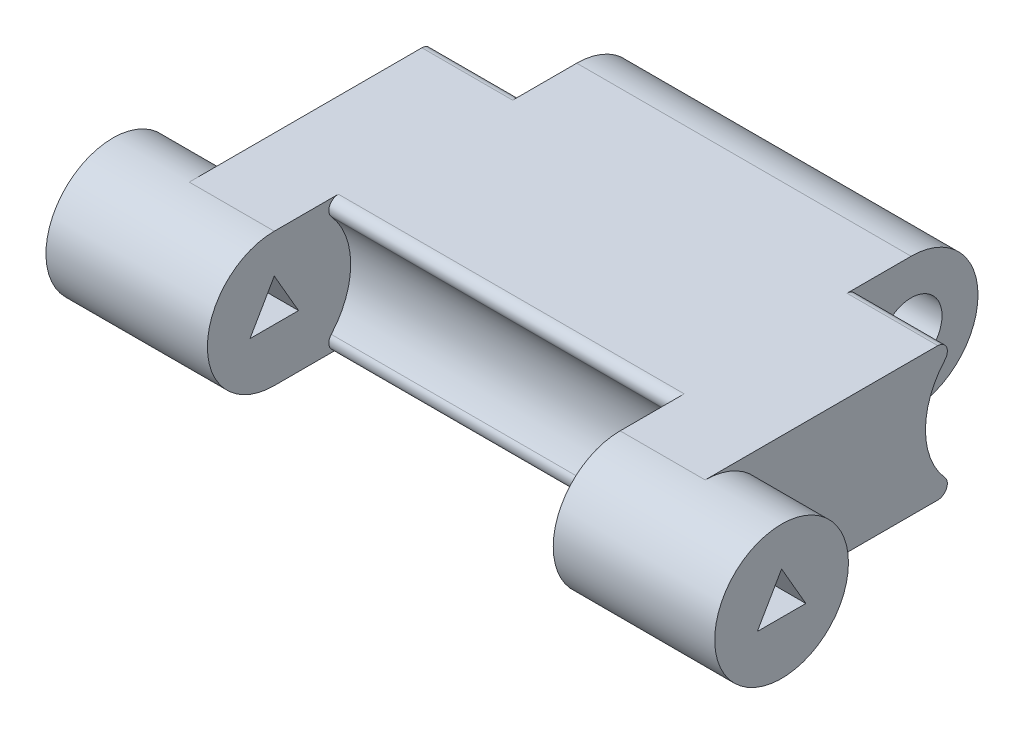
SolidWorks part; units mm, degrees
ref_plane "Спереди" through (0, 0, 0) normal (0, 0, 1) x (1, 0, 0)
ref_plane "Сверху" through (0, 0, 0) normal (0, 1, 0) x (1, 0, 0)
ref_plane "Справа" through (0, 0, 0) normal (1, 0, 0) x (0, 0, -1)
sketch "Эскиз1" plane through (0, 0, 0) normal (1, 0, 0) x (0, 0, -1)
  line L0 (-7.765, 3.5) -> (7.765, 3.5) construction
  line L1 (-7.765, 7) -> (7.765, 7)
  line L2 (-7.765, 0) -> (7.765, 0)
  arc A0 (-7.765, 7) -> (-7.765, 0) centre (-7.765, 3.5) ccw
  arc A1 (7.765, 0) -> (7.765, 7) centre (7.765, 3.5) ccw
  point P2 (0, 3.5)
  dimension "D1" = 15.53
  dimension "D2" = 7
extrude "Бобышка-Вытянуть1" add sketch "Эскиз1" along normal mid plane 35
sketch "Эскиз3" plane through (17.5, 0, 0) normal (1, 0, 0) x (0, 0, -1)
  line L0 (7.765, 7) -> (-7.765, 7) construction
  line L1 (-12, 8) -> (12, 8)
  line L2 (-12, 8) -> (-12, -1)
  line L3 (-12, -1) -> (12, -1)
  line L4 (12, 8) -> (12, -1)
  line L5 (-12, 8) -> (12, -1) construction
  line L6 (-12, -1) -> (12, 8) construction
  line L7 (-7.765, 0) -> (7.765, 0) construction
  circle A0 centre (-7.765, 3.5) radius 3.5
  arc A1 (-7.765, 7) -> (-7.765, 0) centre (-7.765, 3.5) ccw construction
  point P9 (0, 3.5)
  dimension "D1" = 1
  dimension "D2" = 1
  dimension "D3" = 12
  dimension "D4" = 24
extrude "Вырез-Вытянуть1" cut sketch "Эскиз3" against normal blind 4
mirror "Зеркальное отражение1" about plane through (0, 0, 0) normal (1, 0, 0) of "Вырез-Вытянуть1"
sketch "Эскиз6" plane through (0, 0, 0) normal (1, 0, 0) x (0, 0, -1)
  circle A0 centre (-7.765, 3.5) radius 4
  circle A1 centre (-7.765, 3.5) radius 3.5 construction
  dimension "D1" = 8
extrude "Вырез-Вытянуть2" cut sketch "Эскиз6" against normal mid plane 18.1
sketch "Эскиз7" plane through (13.5, 0, 0) normal (1, 0, 0) x (0, 0, -1)
  circle A0 centre (7.765, 3.5) radius 4
  arc A1 (7.765, 0) -> (7.765, 7) centre (7.765, 3.5) ccw construction
  dimension "D2" = 8
  dimension "D1" = 0
extrude "Вырез-Вытянуть3" cut sketch "Эскиз7" against normal blind 4.75
mirror "Зеркальное отражение2" about plane through (0, 0, 0) normal (1, 0, 0) of "Вырез-Вытянуть3"
sketch "Эскиз8" plane through (17.5, 0, 0) normal (1, 0, 0) x (0, 0, -1)
  line L0 (-9.0352, 2.7667) -> (-7.765, 4.9667)
  line L1 (-7.765, 4.9667) -> (-6.4948, 2.7667)
  line L2 (-6.4948, 2.7667) -> (-9.0352, 2.7667)
  circle A1 centre (7.765, 3.5) radius 1.6167
  arc A2 (7.765, 0) -> (7.765, 7) centre (7.765, 3.5) ccw construction
  circle A4 centre (-7.765, 3.5) radius 1.4667 construction
  circle A5 centre (7.765, 3.5) radius 1.4667 construction
  dimension "D1" = 0.15
  dimension "D2" = 2.2
extrude "Вырез-Вытянуть4" cut sketch "Эскиз8" against normal through all
fillet "Скругление1" radius 0.5 6 edges at (-11.125, 0, -5.8285) (-11.125, 7, -5.8285) (0, 7, 5.8285) (0, 0, 5.8285) (11.125, 7, -5.8285) (11.125, 0, -5.8285)
ref_plane "Плоскость4" through (-13.5, 0, 0) normal (-1, 0, 0) x (0, 0, 1)
sketch "Эскиз9" plane through (-17.5, 0, 0) normal (-1, 0, 0) x (0, 0, 1)
  circle A0 centre (7.765, 3.5) radius 0.75
  circle A1 centre (7.765, 3.5) radius 3.5
  circle A2 centre (7.765, 3.5) radius 3.5
  dimension "D2" = 1.5
  dimension "D1" = 0
extrude "Бобышка-Вытянуть2" add sketch "Эскиз9" against normal blind 1
